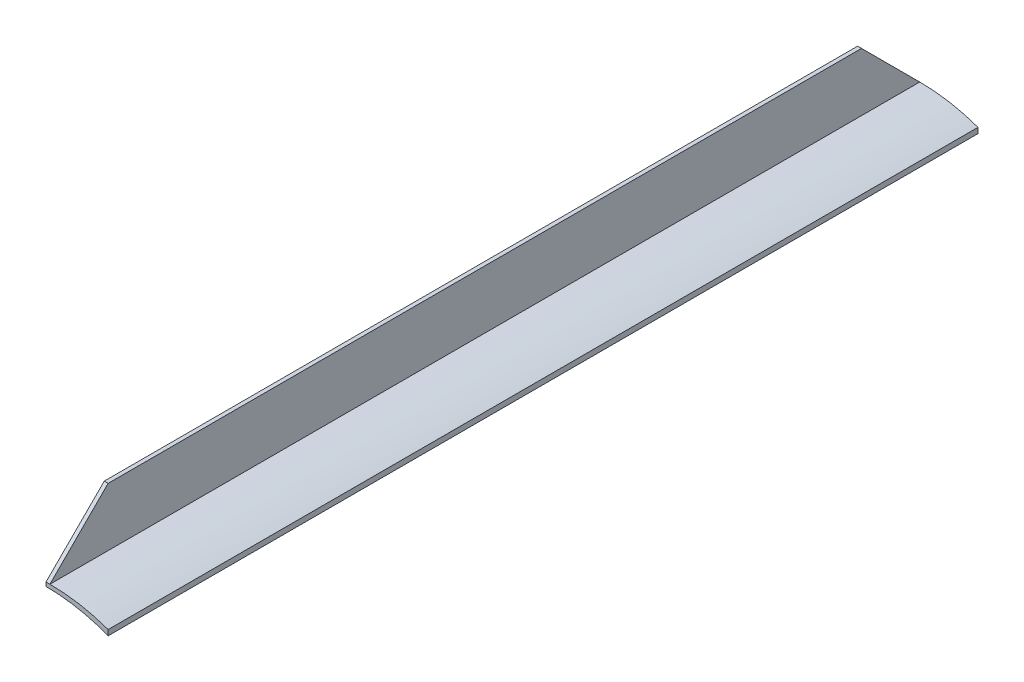
SolidWorks part; units mm, degrees
material "6061-T6 (SS)"
ref_plane "Front Plane" through (0, 0, 0) normal (0, 0, 1) x (1, 0, 0)
ref_plane "Top Plane" through (0, 0, 0) normal (0, 1, 0) x (1, 0, 0)
ref_plane "Right Plane" through (0, 0, 0) normal (1, 0, 0) x (0, 0, -1)
sketch "Sketch1" plane through (0, 0, 0) normal (0, 0, 1) x (1, 0, 0)
  line L0 (0, 0) -> (0, 25.4)
  line L1 (0, 25.4) -> (1.5875, 25.4)
  line L2 (1.5875, 25.4) -> (1.5875, 1.5875)
  line L3 (25.4, -2.5468) -> (25.4, -4.7819)
  arc A0 (0, 0) -> (25.4, -4.7819) centre (0, -69.85) cw
  arc A1 (1.5875, 1.5875) -> (25.4, -2.5468) centre (1.5875, -69.0562) cw
  dimension "D1" = 25.4
  dimension "D5" = 69.85
  dimension "D6" = 70.6437
  dimension "D2" = 23.8125
  dimension "D3" = 1.5875
  dimension "D4" = 25.4
extrude "Extrude1" add sketch "Sketch1" along normal mid plane 355.6
ref_plane "Plane2" through (0, 0, 0) normal (0, 0, -1) x (-1, 0, 0)
sketch "Sketch2" plane through (0, 0, 0) normal (-1, 0, 0) x (0, 0, 1)
  line L0 (177.8, 25.4) -> (153.9875, 25.4)
  line L1 (177.8, 25.4) -> (-177.8, 25.4) construction
  line L2 (153.9875, 25.4) -> (177.8, 1.5875)
  line L3 (177.8, 25.4) -> (177.8, 0) construction
  line L4 (177.8, 1.5875) -> (177.8, 25.4)
  dimension "D1" = 1.5875
extrude "Extrude2" cut sketch "Sketch2" against normal blind 387.35
mirror "Mirror2" about plane through (0, 0, 0) normal (0, 0, -1) of "Extrude2"
